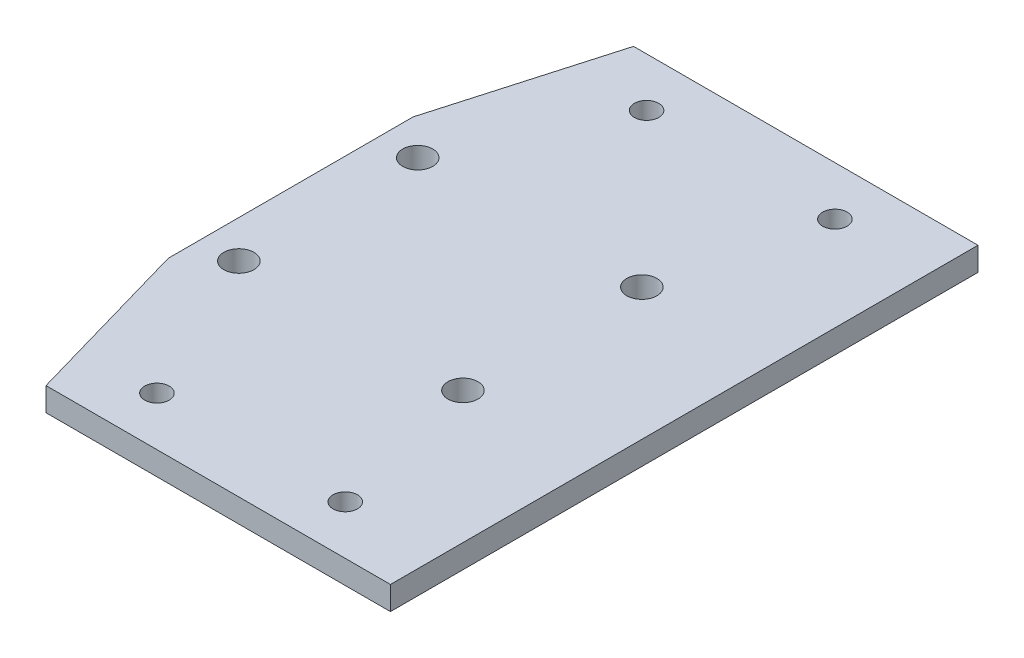
SolidWorks part; units mm, degrees
ref_plane "Front Plane" through (0, 0, 0) normal (0, 0, 1) x (1, 0, 0)
ref_plane "Top Plane" through (0, 0, 0) normal (0, 1, 0) x (1, 0, 0)
ref_plane "Right Plane" through (0, 0, 0) normal (1, 0, 0) x (0, 0, -1)
sketch "Sketch1" plane through (0, 0, 0) normal (0, 1, 0) x (1, 0, 0)
  line L0 (-134.5944, -15.7543) -> (41.7895, -15.7543) construction
  line L1 (-54.9738, 23.8697) -> (2.1762, 23.8697)
  line L2 (-54.9738, 23.8697) -> (-54.9738, -55.3783)
  line L3 (-54.9738, -55.3783) -> (2.1762, -55.3783)
  line L4 (2.1762, 23.8697) -> (2.1762, -55.3783)
  point P6 (-54.9738, -15.7543)
  dimension "D1" = 79.248
  dimension "D2" = 57.15
extrude "Boss-Extrude1" add sketch "Sketch1" against normal blind 3.175
sketch "Sketch2" plane through (0, 0, 0) normal (0, 1, 0) x (1, 0, 0)
  line L0 (-35.9238, -48.7743) -> (-10.5238, -48.7743) construction
  line L1 (-10.5238, -48.7743) -> (-10.5238, 17.2657) construction
  line L2 (-10.5238, 17.2657) -> (-35.9238, 17.2657) construction
  line L3 (-35.9238, 17.2657) -> (-35.9238, -48.7743) construction
  line L4 (-35.9238, -55.3783) -> (-35.9238, -48.7743) construction
  line L5 (-54.9738, -55.3783) -> (2.1762, -55.3783) construction
  line L6 (-35.9238, 17.2657) -> (-35.9238, 23.8697) construction
  line L7 (2.1762, 23.8697) -> (-54.9738, 23.8697) construction
  line L8 (2.1762, -55.3783) -> (2.1762, 23.8697) construction
  circle A0 centre (-35.9238, -48.7743) radius 1.651
  circle A1 centre (-35.9238, 17.2657) radius 1.651
  circle A2 centre (-10.5238, -48.7743) radius 1.651
  circle A3 centre (-10.5238, 17.2657) radius 1.651
  dimension "D3" = 3.302
  dimension "D1" = 25.4
  dimension "D2" = 66.04
  dimension "D4" = 12.7
extrude "Cut-Extrude1" cut sketch "Sketch2" against normal through all
sketch "Sketch3" plane through (0, 0, 0) normal (0, 1, 0) x (1, 0, 0)
  line L0 (-45.8298, -27.8193) -> (-45.8298, -3.6893) construction
  line L1 (-45.8298, -3.6893) -> (-15.6038, -3.6893) construction
  line L2 (-15.6038, -3.6893) -> (-15.6038, -27.8193) construction
  line L3 (-15.6038, -27.8193) -> (-45.8298, -27.8193) construction
  line L4 (-10.5238, -48.7743) -> (-15.6038, -27.8193) construction
  line L5 (-15.6038, -3.6893) -> (-10.5238, 17.2657) construction
  circle A0 centre (-45.8298, -3.6893) radius 2.032
  circle A1 centre (-15.6038, -3.6893) radius 2.032
  circle A2 centre (-45.8298, -27.8193) radius 2.032
  circle A3 centre (-15.6038, -27.8193) radius 2.032
  dimension "D3" = 4.064
  dimension "D1" = 30.226
  dimension "D2" = 24.13
  dimension "D4" = 5.08
extrude "Cut-Extrude2" cut sketch "Sketch3" against normal through all
sketch "Sketch4" plane through (0, 0, 0) normal (0, 1, 0) x (1, 0, 0)
  line L0 (-50.9098, -32.2643) -> (-50.9098, 0.7557)
  line L1 (-50.9098, 0.7557) -> (-40.9211, 35.5903)
  line L2 (-40.9211, 35.5903) -> (-90.516, 35.5903)
  line L3 (-90.516, 35.5903) -> (-90.516, -67.0988)
  line L4 (-90.516, -67.0988) -> (-50.9098, -67.0988)
  line L5 (-50.9098, -67.0988) -> (-40.9211, -67.0988)
  line L6 (-40.9211, -67.0988) -> (-50.9098, -32.2643)
  line L7 (-50.9098, 0.7557) -> (-50.9098, 35.5903) construction
  line L8 (-50.9098, -32.2643) -> (-50.9098, -67.0988) construction
  line L9 (2.1762, -15.7543) -> (-104.5506, -15.7543) construction
  line L10 (2.1762, -55.3783) -> (2.1762, 23.8697) construction
  circle A2 centre (-45.8298, -3.6893) radius 2.032 construction
  point P12 (2.1762, -15.7543)
  point P13 (-50.9098, -15.7543)
  dimension "D2" = 16
  dimension "D1" = 33.02
  dimension "D3" = 5.08
extrude "Cut-Extrude3" cut sketch "Sketch4" against normal through all
